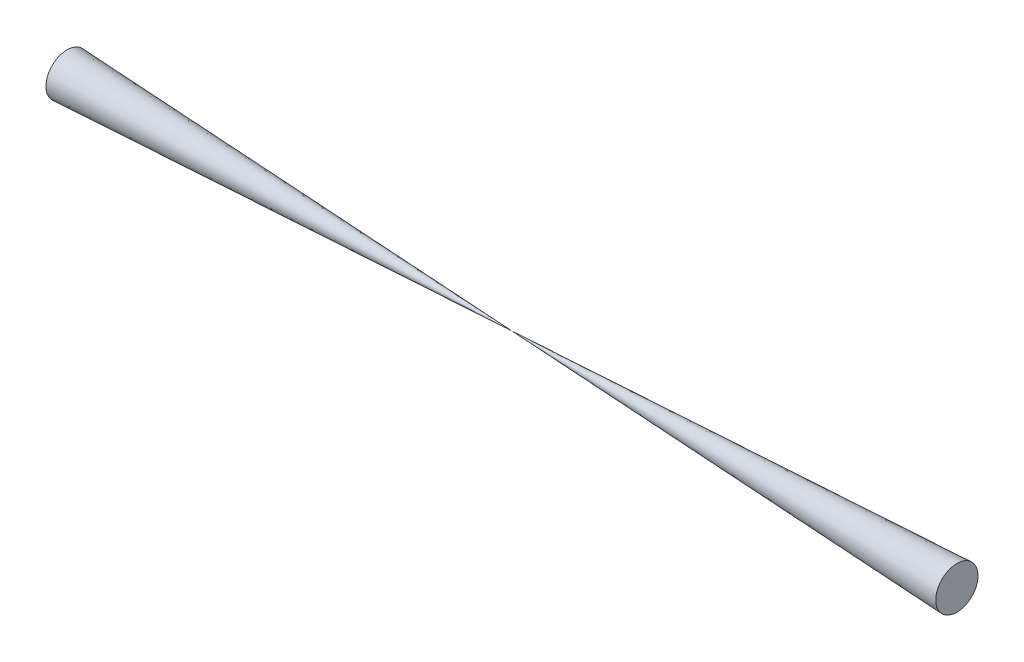
SolidWorks part; units mm, degrees
ref_plane "前视基准面" through (0, 0, 0) normal (0, 0, 1) x (1, 0, 0)
ref_plane "上视基准面" through (0, 0, 0) normal (0, 1, 0) x (1, 0, 0)
ref_plane "右视基准面" through (0, 0, 0) normal (1, 0, 0) x (0, 0, -1)
sketch "草图1" plane through (0, 0, 0) normal (0, 1, 0) x (1, 0, 0)
  line L0 (0, 0) -> (0, 0.005)
  line L1 (0, 0.005) -> (200, 9.5)
  line L2 (200, 9.5) -> (200, 0)
  line L3 (200, 0) -> (0, 0)
  dimension "D1" = 0.005
  dimension "D2" = 9.5
  dimension "D3" = 200
revolve "旋转1" add sketch "草图1" angle 360 about L3
mirror "镜向1" about plane through (0, 0, 0) normal (-1, 0, 0) of "旋转1"
sketch "草图2" plane through (0, 0, 0) normal (0, 0, 1) x (1, 0, 0)
  line L0 (0, 1.237) -> (0, -1.3272) construction
  line L1 (-0.2735, 0) -> (0.3601, 0) construction
